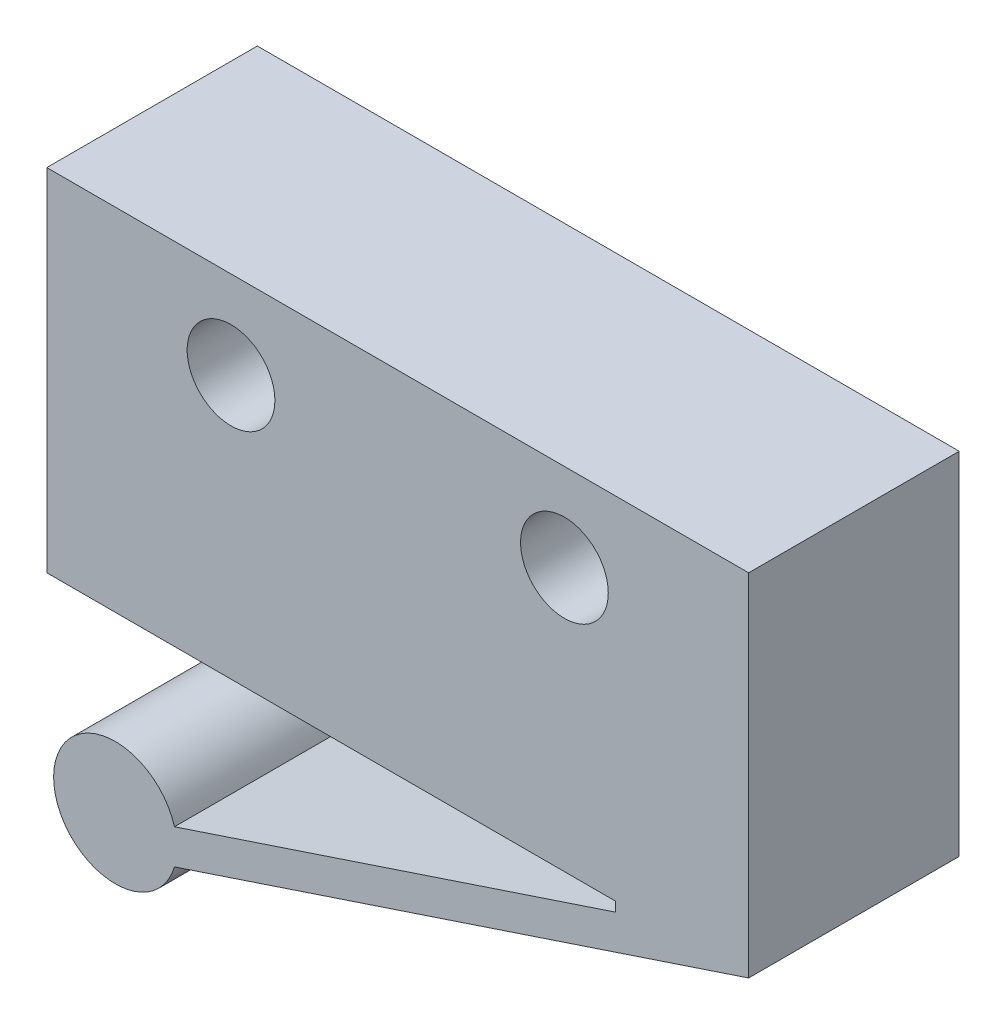
SolidWorks part; units mm, degrees
ref_plane "Plan de face" through (0, 0, 0) normal (0, 0, 1) x (1, 0, 0)
ref_plane "Plan de dessus" through (0, 0, 0) normal (0, 1, 0) x (1, 0, 0)
ref_plane "Plan de droite" through (0, 0, 0) normal (1, 0, 0) x (0, 0, -1)
sketch "Esquisse1" plane through (0, 0, 0) normal (0, 0, 1) x (1, 0, 0)
  line L0 (14.75, 2.5) -> (-5.25, 2.5)
  line L1 (-5.25, 2.5) -> (-5.25, -7.5)
  line L2 (-5.25, -7.5) -> (10.9568, -7.5)
  line L3 (10.9568, -7.5) -> (10.9568, -7.771)
  line L4 (10.9568, -7.771) -> (-1.6117, -11.9487)
  line L5 (14.75, 2.5) -> (14.75, -7.5)
  line L6 (-1.612, -12.9386) -> (14.75, -7.5)
  arc A0 (-1.6117, -11.9487) -> (-1.612, -12.9386) centre (-3.2982, -12.4432) ccw
  circle A1 centre (0, 0) radius 1.25
  circle A2 centre (9.5, 0) radius 1.25
  point P13 (0, 0)
  point P15 (0, 0)
  point P18 (-1.3007, -17.4917)
  dimension "D5" = 2.5
  dimension "D6" = 2.5
  dimension "D12" = 1.7575
  dimension "D1" = 20
  dimension "D2" = 10
  dimension "D3" = 10
  dimension "D4" = 2.5
  dimension "D7" = 2.5
  dimension "D8" = 9.5
  dimension "D9" = 5.25
  dimension "D10" = 4.9432
  dimension "D11" = 1.9518
extrude "Boss.-Extru.1" add sketch "Esquisse1" along normal blind 6
